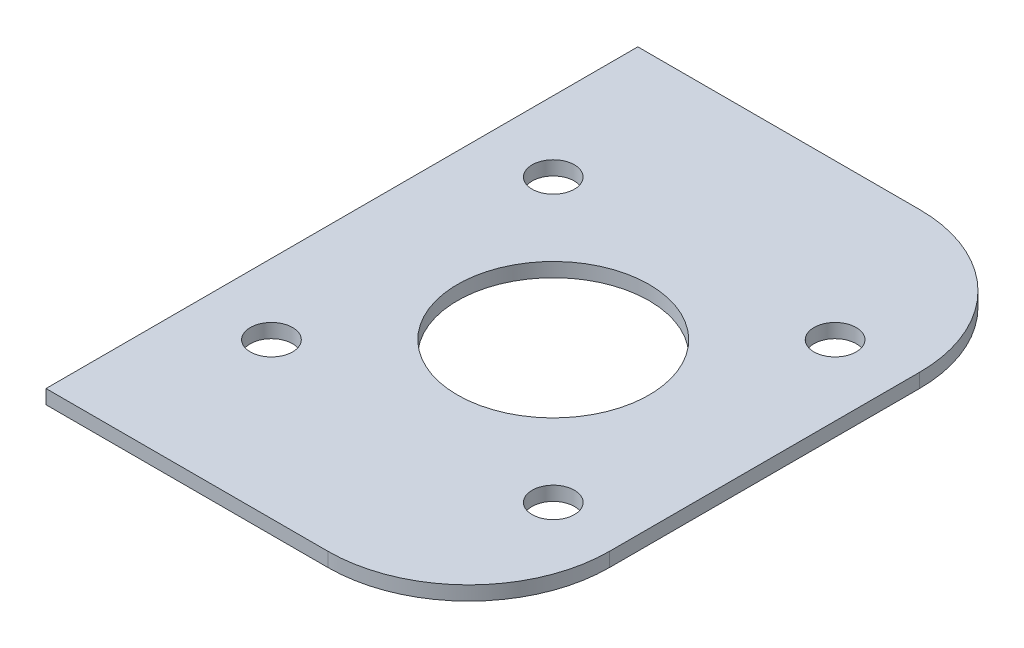
SolidWorks part; units mm, degrees
material "1060 Alloy"
ref_plane "Front Plane" through (0, 0, 0) normal (0, 0, 1) x (1, 0, 0)
ref_plane "Top Plane" through (0, 0, 0) normal (0, 1, 0) x (1, 0, 0)
ref_plane "Right Plane" through (0, 0, 0) normal (1, 0, 0) x (0, 0, -1)
sketch "Sketch2" plane through (0, 0, 0) normal (0, 1, 0) x (1, 0, 0)
  line L1 (-15, 21) -> (15, 21)
  line L2 (-15, 21) -> (-15, -21)
  line L3 (-15, -21) -> (15, -21)
  line L4 (15, 21) -> (15, -21)
  line L5 (-15, 21) -> (15, -21) construction
  line L6 (-15, -21) -> (15, 21) construction
  circle A0 centre (0, 0) radius 6.8
  point P0 (0, 0)
  dimension "D3" = 13.6
  dimension "D1" = 42
  dimension "D2" = 30
extrude "Boss-Extrude1" add sketch "Sketch2" along normal blind 1
fillet "Fillet1" radius 10 2 edges at (15, 0.5, -21) (15, 0.5, 21)
sketch "Sketch3" plane through (0, 1, 0) normal (0, 1, 0) x (1, 0, 0)
  circle A0 centre (-10, 10) radius 1.5
  circle A1 centre (10, 10) radius 1.5
  circle A2 centre (10, -10) radius 1.5
  circle A3 centre (-10, -10) radius 1.5
  point P0 (0, 0)
  dimension "D3" = 3
  dimension "D4" = 3
  dimension "D5" = 3
  dimension "D6" = 3
  dimension "D1" = 20
  dimension "D2" = 20
extrude "Cut-Extrude1" cut sketch "Sketch3" against normal blind 1
